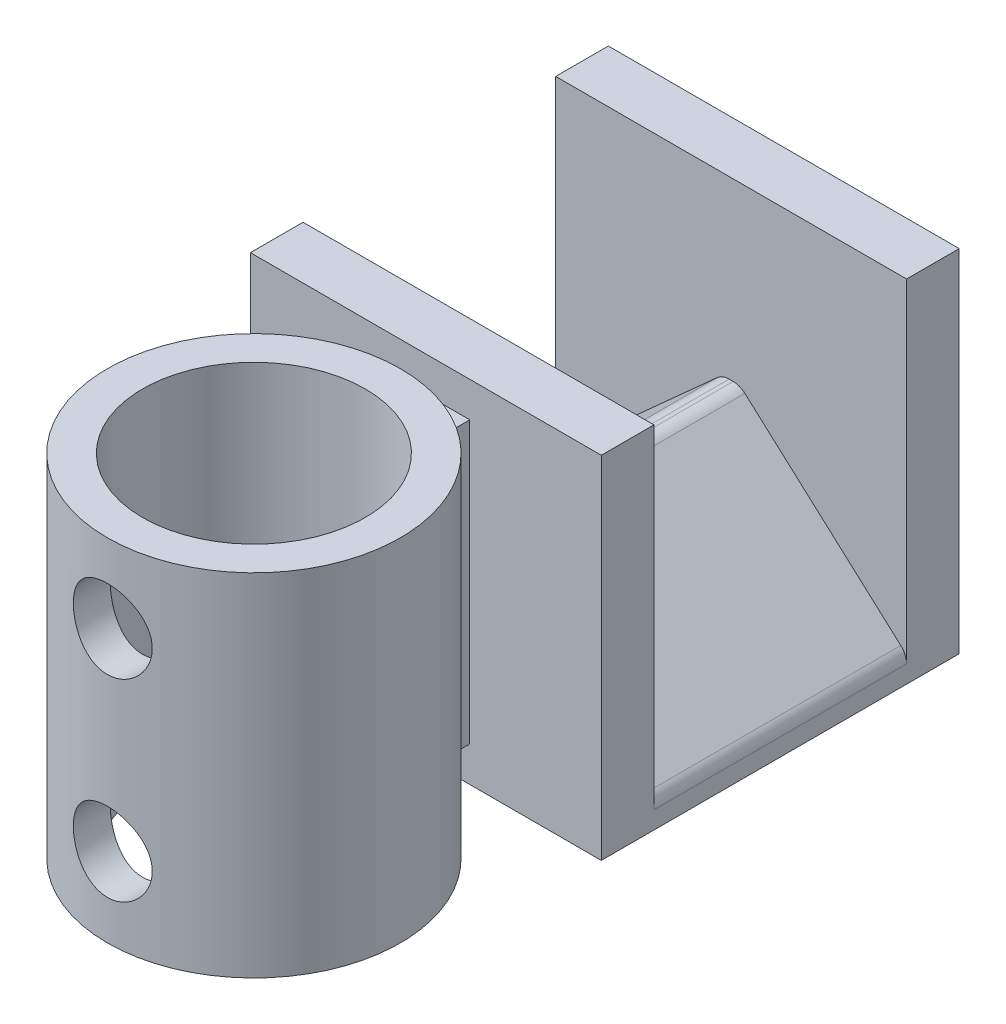
SolidWorks part; units mm, degrees
ref_plane "Front Plane" through (0, 0, 0) normal (0, 0, 1) x (1, 0, 0)
ref_plane "Top Plane" through (0, 0, 0) normal (0, 1, 0) x (1, 0, 0)
ref_plane "Right Plane" through (0, 0, 0) normal (1, 0, 0) x (0, 0, -1)
sketch "Sketch2" plane through (0, 0, 0) normal (0, 0, 1) x (1, 0, 0)
  line L1 (-10, -5) -> (10, -5)
  line L2 (-10, -5) -> (-10, 5)
  line L3 (-10, 5) -> (10, 5)
  line L4 (10, -5) -> (10, 5)
  line L5 (-10, -5) -> (10, 5) construction
  line L6 (-10, 5) -> (10, -5) construction
  point P0 (0, 0)
  dimension "D1" = 10
  dimension "D2" = 20
extrude "Boss-Extrude1" add sketch "Sketch2" along normal mid plane 14.4
chamfer "Chamfer1" distance 9.5 angle 42 2 edges at (10, 5, 0) (-10, 5, 0)
fillet "Fillet3" radius 1 4 edges at (-10, -3.5538, 0) (10, -3.5538, 0) (0.5, 5, 0) (-0.5, 5, 0)
sketch "Sketch3" plane through (0, 0, 7.2) normal (0, 0, 1) x (1, 0, 0)
  line L0 (-10, -5) -> (10, -5) construction
  line L1 (-10, 15) -> (10, 15)
  line L2 (-10, 15) -> (-10, -5)
  line L3 (-10, -5) -> (10, -5)
  line L4 (10, 15) -> (10, -5)
  line L5 (-10, 15) -> (10, -5) construction
  line L6 (-10, -5) -> (10, 15) construction
  point P0 (0, 5)
  dimension "D1" = 20
  dimension "D2" = 20
extrude "Boss-Extrude2" add sketch "Sketch3" along normal blind 3
mirror "Mirror1" about plane through (0, 0, 0) normal (0, 0, 1) of "Boss-Extrude2"
sketch "Sketch6" plane through (0, 0, 0) normal (0, 1, 0) x (1, 0, 0)
  circle A0 centre (0, -20) radius 6.35
  circle A1 centre (0, -20) radius 8.35
  dimension "D1" = 12.7
  dimension "D2" = 2
  dimension "D3" = 20
extrude "Boss-Extrude3" add sketch "Sketch6" along normal up to surface and the other way up to surface separate body up to face at (0, 15, 8.7) other way up to face at (0, -5, 0)
sketch "Sketch5" plane through (0, 0, 10.2) normal (0, 0, 1) x (1, 0, 0)
  line L0 (-10, -5) -> (10, -5) construction
  line L1 (-2.5, 13) -> (2.5, 13)
  line L2 (-2.5, 13) -> (-2.5, -3)
  line L3 (-2.5, -3) -> (2.5, -3)
  line L4 (2.5, 13) -> (2.5, -3)
  line L5 (-2.5, 13) -> (2.5, -3) construction
  line L6 (-2.5, -3) -> (2.5, 13) construction
  line L7 (10, 15) -> (-10, 15) construction
  point P0 (0, 5)
  dimension "D1" = 2
  dimension "D2" = 2
  dimension "D3" = 5
extrude "Boss-Extrude4" add sketch "Sketch5" along normal up to surface (1.833 mm away)
ref_plane "Plane1" through (0, 0, 20) normal (0, 0, 1) x (1, 0, 0)
sketch "Sketch7" plane through (0, 0, 20) normal (0, 0, 1) x (1, 0, 0)
  line L0 (-8.35, -5) -> (8.35, -5) construction
  line L1 (6.35, 15) -> (-6.35, 15) construction
  circle A0 centre (0, 10.5) radius 2.25
  circle A1 centre (0, -0.5) radius 2.25
  dimension "D1" = 4.5
  dimension "D2" = 4.5
  dimension "D3" = 4.5
  dimension "D4" = 4.5
extrude "Cut-Extrude1" cut sketch "Sketch7" along normal up to surface (8.0412 mm away)
